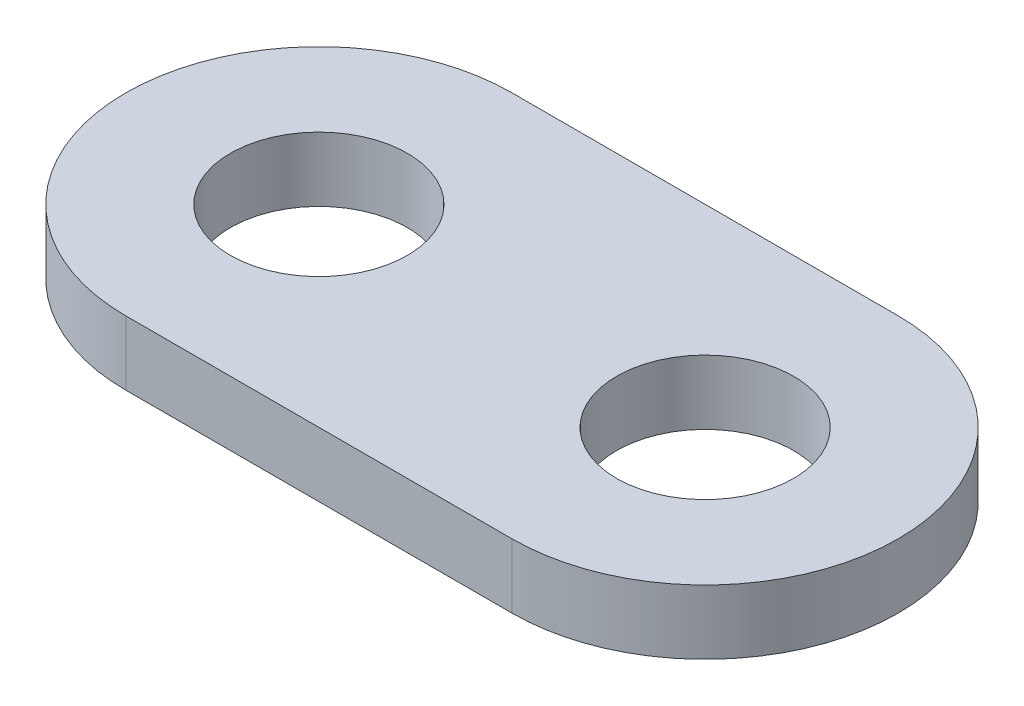
SolidWorks part; units mm, degrees
ref_plane "Front Plane" through (0, 0, 0) normal (0, 0, 1) x (1, 0, 0)
ref_plane "Top Plane" through (0, 0, 0) normal (0, 1, 0) x (1, 0, 0)
ref_plane "Right Plane" through (0, 0, 0) normal (1, 0, 0) x (0, 0, -1)
sketch "Sketch1" plane through (0, 0, 0) normal (0, 1, 0) x (1, 0, 0)
  line L0 (-6, 0) -> (6, 0) construction
  line L1 (-6, 6) -> (6, 6)
  line L2 (-6, -6) -> (6, -6)
  line L3 (-1, 6) -> (-1, -6)
  line L4 (1, -6) -> (1, 6)
  circle A0 centre (-6, 0) radius 2.75
  circle A1 centre (6, 0) radius 2.75
  circle A2 centre (-6, 0) radius 5 construction
  circle A3 centre (6, 0) radius 5 construction
  circle A4 centre (-6, 0) radius 6
  circle A5 centre (6, 0) radius 6
  dimension "D1" = 5.5
  dimension "D2" = 1
  dimension "D3" = 10
extrude "Boss-Extrude1" add sketch "Sketch1" along normal blind 2 contours A4 L3 L1 | A5 L4 L1 L3 A4 | A5 L1 L4 | A5 L4 A1 | L4 A5 | L3 A4 | A4 L3 A0 | A4 L2 L3 | A5 A4 L3 L2 L4 | A5 L4 L2
